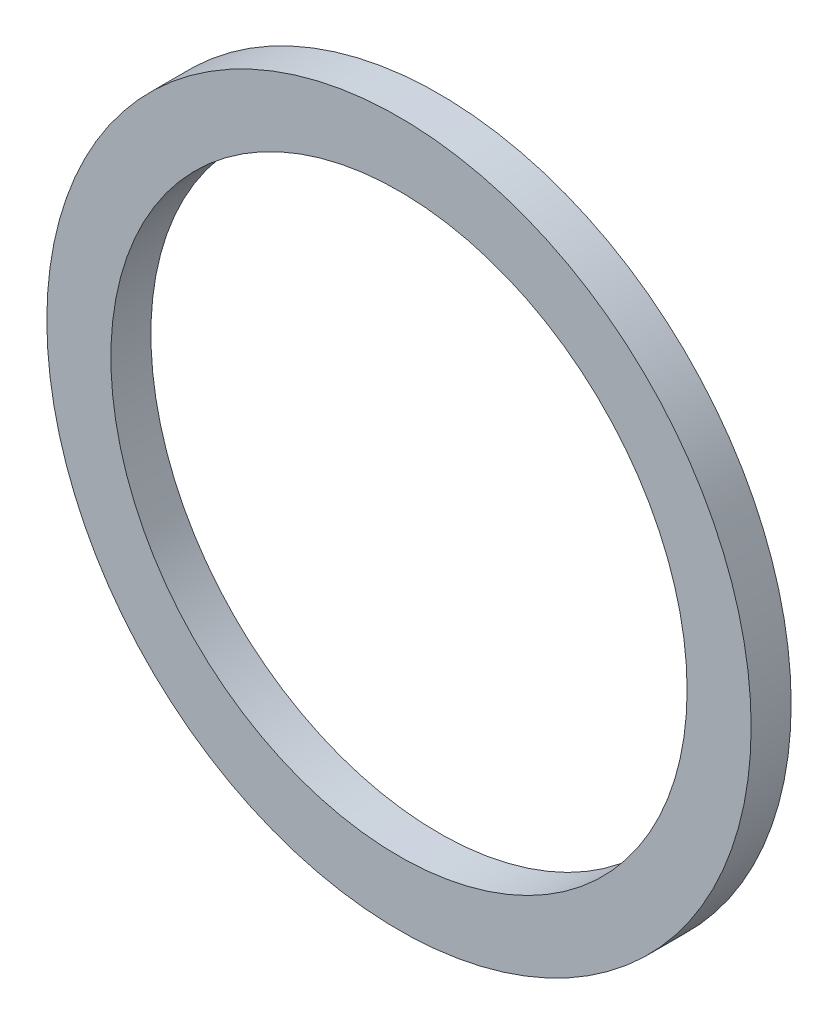
SolidWorks part; units mm, degrees
ref_plane "Plan1" through (0, 0, 0) normal (0, 0, 1) x (1, 0, 0)
ref_plane "Plan2" through (0, 0, 0) normal (0, 1, 0) x (1, 0, 0)
ref_plane "Plan3" through (0, 0, 0) normal (1, 0, 0) x (0, 0, -1)
sketch "Esquisse1" plane through (0, 0, 0) normal (0, 0, 1) x (1, 0, 0)
  circle A0 centre (0, 0) radius 11
  circle A1 centre (0, 0) radius 9
  dimension "D1" = 18
  dimension "D2" = 22
extrude "Base-Extrusion" add sketch "Esquisse1" along normal blind 1.25
